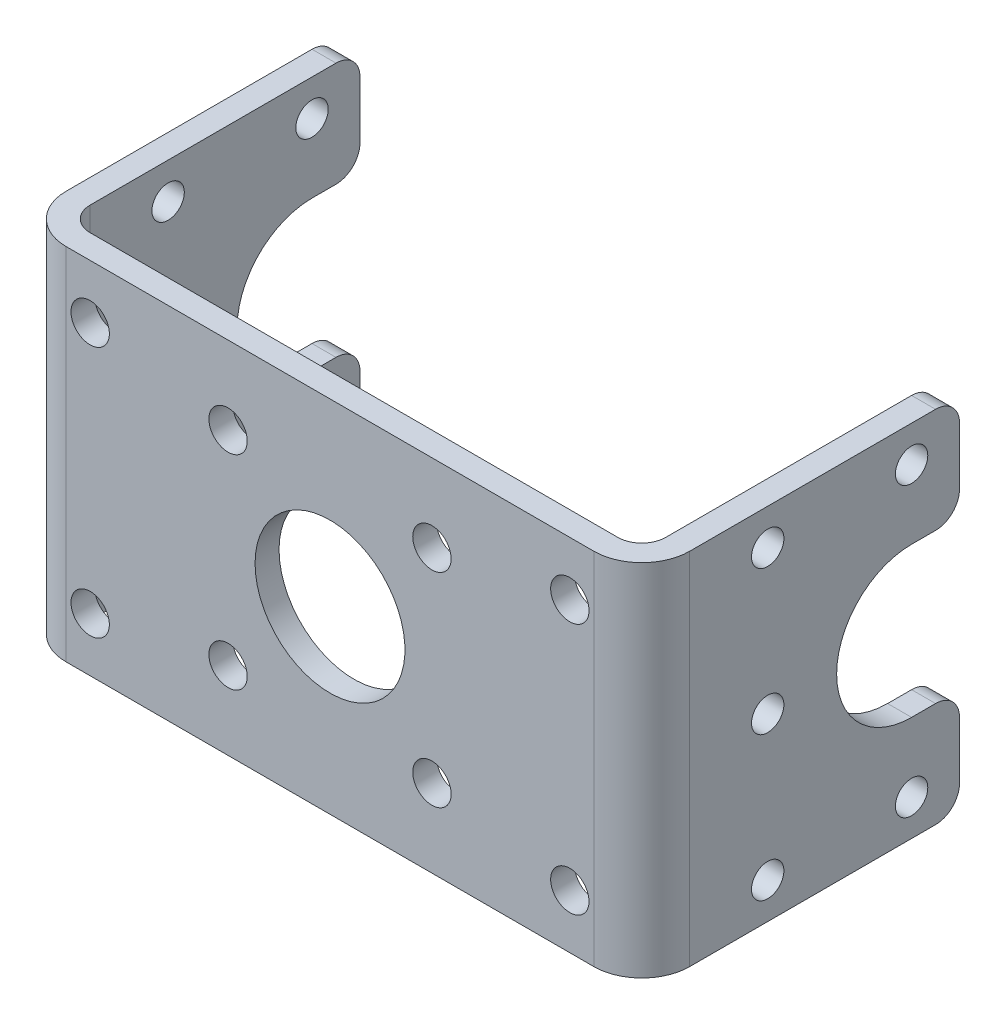
SolidWorks part; units mm, degrees
ref_plane "前视基准面" through (0, 0, 0) normal (0, 0, 1) x (1, 0, 0)
ref_plane "上视基准面" through (0, 0, 0) normal (0, 1, 0) x (1, 0, 0)
ref_plane "右视基准面" through (0, 0, 0) normal (1, 0, 0) x (0, 0, -1)
sketch "草图1" plane through (0, 0, 0) normal (0, 1, 0) x (1, 0, 0)
  line L0 (0, 0) -> (0, 77.3148) construction
  line L1 (0, 0) -> (22, 0)
  line L2 (26, 4) -> (26, 26.5)
  line L3 (0, 2) -> (22, 2)
  line L4 (24, 4) -> (24, 26.5)
  line L5 (26, 26.5) -> (24, 26.5)
  line L6 (-26, 26.5) -> (-24, 26.5)
  line L7 (-24, 4) -> (-24, 26.5)
  line L8 (0, 2) -> (-22, 2)
  line L9 (-26, 4) -> (-26, 26.5)
  line L10 (0, 0) -> (-22, 0)
  line L11 (0, 2) -> (24, 2) construction
  line L12 (24, 2) -> (24, 26.5) construction
  line L13 (0, 0) -> (26, 0) construction
  line L14 (26, 0) -> (26, 26.5) construction
  arc A0 (22, 2) -> (24, 4) centre (22, 4) ccw
  arc A1 (-22, 2) -> (-24, 4) centre (-22, 4) cw
  arc A2 (22, 0) -> (26, 4) centre (22, 4) ccw
  arc A3 (-22, 0) -> (-26, 4) centre (-22, 4) cw
  point P15 (24, 2)
  point P18 (-24, 2)
  point P22 (26, 0)
  point P25 (-26, 0)
  dimension "D4" = 2
  dimension "D5" = 4
  dimension "D2" = 48
  dimension "D3" = 26.5
  dimension "D1" = 2
extrude "凸台-拉伸1" add sketch "草图1" along normal mid plane 30
sketch "草图2" plane through (0, 0, -2) normal (0, 0, -1) x (-1, 0, 0)
  line L1 (-8.5, -8.5) -> (8.5, -8.5) construction
  line L2 (-8.5, -8.5) -> (-8.5, 8.5) construction
  line L3 (-8.5, 8.5) -> (8.5, 8.5) construction
  line L4 (8.5, -8.5) -> (8.5, 8.5) construction
  line L5 (-8.5, -8.5) -> (8.5, 8.5) construction
  line L6 (-8.5, 8.5) -> (8.5, -8.5) construction
  line L7 (-20, -10.5) -> (20, -10.5) construction
  line L8 (-20, -10.5) -> (-20, 10.5) construction
  line L9 (-20, 10.5) -> (20, 10.5) construction
  line L10 (20, -10.5) -> (20, 10.5) construction
  line L11 (-20, -10.5) -> (20, 10.5) construction
  line L12 (-20, 10.5) -> (20, -10.5) construction
  circle A0 centre (20, 10.5) radius 1.6
  circle A1 centre (8.5, 8.5) radius 1.6
  circle A2 centre (-8.5, 8.5) radius 1.6
  circle A3 centre (-20, 10.5) radius 1.6
  circle A4 centre (-20, -10.5) radius 1.6
  circle A5 centre (8.5, -8.5) radius 1.6
  circle A6 centre (-8.5, -8.5) radius 1.6
  circle A7 centre (20, -10.5) radius 1.6
  circle A8 centre (0, 0) radius 6.25
  point P0 (0, 0)
  point P6 (0, 0)
  dimension "D5" = 3.2
  dimension "D6" = 12.5
  dimension "D1" = 17
  dimension "D2" = 17
  dimension "D3" = 21
  dimension "D4" = 40
extrude "切除-拉伸1" cut sketch "草图2" against normal up to vertex (2 mm away)
sketch "草图3" plane through (0, 0, 0) normal (1, 0, 0) x (0, 0, -1)
  line L0 (0, 0) -> (22.5, 0) construction
  line L1 (22.5, 6.25) -> (26.5, 6.25)
  line L2 (26.5, 15) -> (26.5, -15) construction
  line L3 (22.5, 12) -> (22.5, -12) construction
  line L4 (22.5, 12) -> (10.5, 12) construction
  line L5 (22.5, -6.25) -> (26.5, -6.25)
  line L6 (26.5, 6.25) -> (26.5, -6.25)
  arc A0 (22.5, 6.25) -> (22.5, -6.25) centre (22.5, 0) ccw
  circle A1 centre (10.5, 12) radius 1.35
  circle A2 centre (22.5, 12) radius 1.35
  circle A3 centre (10.5, 0) radius 1.35
  circle A4 centre (22.5, -12) radius 1.35
  circle A5 centre (10.5, -12) radius 1.35
  point P10 (22.5, 0)
  dimension "D1" = 2.7
  dimension "D2" = 24
  dimension "D5" = 6.25
  dimension "D3" = 22.5
  dimension "D4" = 12
extrude "切除-拉伸2" cut sketch "草图3" against normal mid plane 63
fillet "圆角1" radius 2 8 edges at (25, -15, -26.5) (25, -6.25, -26.5) (25, 15, -26.5) (25, 6.25, -26.5) (-25, 15, -26.5) (-25, 6.25, -26.5) (-25, -6.25, -26.5) (-25, -15, -26.5)
